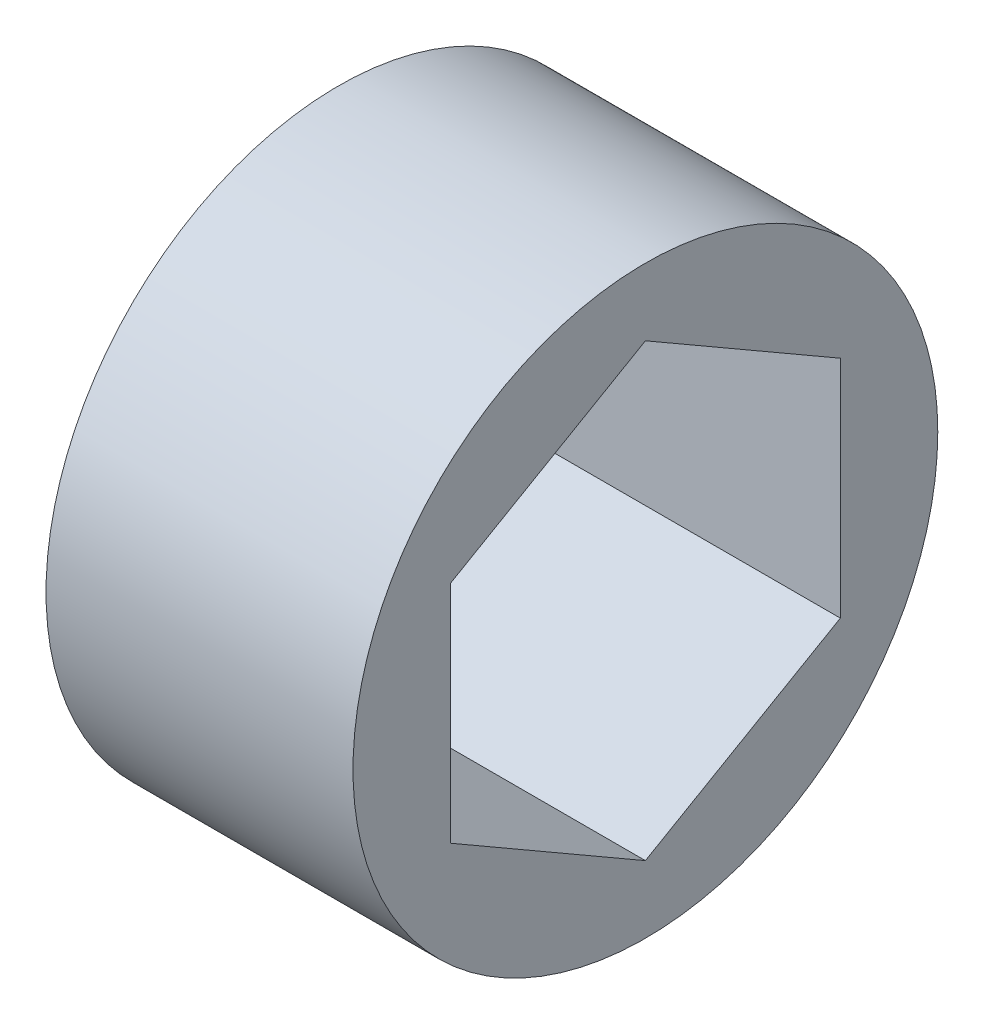
SolidWorks part; units mm, degrees
ref_plane "Front Plane" through (0, 0, 0) normal (0, 0, 1) x (1, 0, 0)
ref_plane "Top Plane" through (0, 0, 0) normal (0, 1, 0) x (1, 0, 0)
ref_plane "Right Plane" through (0, 0, 0) normal (1, 0, 0) x (0, 0, -1)
sketch "Sketch1" plane through (0, 0, 0) normal (1, 0, 0) x (0, 0, -1)
  line L1 (0, 7.3323) -> (-6.35, 3.6662)
  line L2 (-6.35, 3.6662) -> (-6.35, -3.6662)
  line L3 (-6.35, -3.6662) -> (0, -7.3323)
  line L4 (0, -7.3323) -> (6.35, -3.6662)
  line L5 (6.35, -3.6662) -> (6.35, 3.6662)
  line L6 (6.35, 3.6662) -> (0, 7.3323)
  circle A0 centre (0, 0) radius 9.525
  circle A1 centre (0, 0) radius 6.35 construction
  dimension "D2" = 19.05
  dimension "D1" = 12.7
extrude "Boss-Extrude1" add sketch "Sketch1" along normal blind 10
